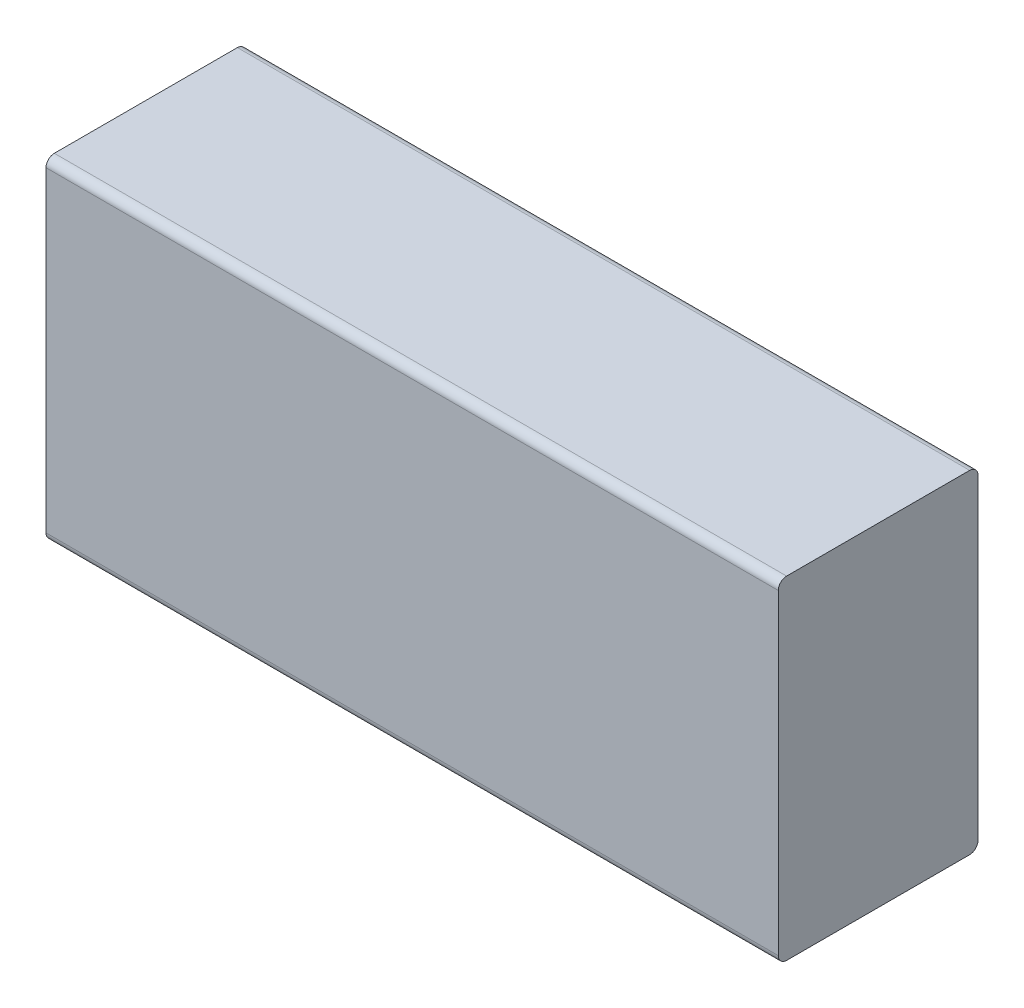
SolidWorks part; units mm, degrees
ref_plane "Front" through (0, 0, 0) normal (0, 0, 1) x (1, 0, 0)
ref_plane "Top" through (0, 0, 0) normal (0, 1, 0) x (1, 0, 0)
ref_plane "Right" through (0, 0, 0) normal (1, 0, 0) x (0, 0, -1)
sketch "Sketch1" plane through (0, 0, 0) normal (0, 0, 1) x (1, 0, 0)
  line L0 (0, 5) -> (-17, 5)
  line L1 (-17, -5) -> (0, -5)
  line L2 (-17, 5) -> (-17, -5)
  arc A2 (0, 5) -> (0, -5) centre (0, 0) cw
  dimension "b" = 10
  dimension "l" = 22
extrude "Extrude1" add sketch "Sketch1" along normal blind 6
sketch "Sketch2" plane through (0, 0, 0) normal (0, 0, 1) x (1, 0, 0)
  line L2 (5, 5) -> (5, -5)
  line L6 (0, 5) -> (-17, 5)
  line L7 (-17, 5) -> (-17, -5)
  line L8 (-17, -5) -> (0, -5)
  line L9 (5, 5) -> (-17, 5)
  line L10 (-17, 5) -> (-17, -5)
  line L11 (-17, -5) -> (5, -5)
  arc A3 (0, -5) -> (0, 5) centre (0, 0) ccw
  arc A4 (0, -5) -> (0, 5) centre (0, 0) ccw construction
  dimension "D1" = 0
extrude "Extrude2" add sketch "Sketch2" along normal blind 6
fillet "Fillet1" radius 0.25 4 edges at (-6, -5, 0) (-6, -5, 6) (-6, 5, 0) (-6, 5, 6)
equation "\"D1@Extrude2\" = \"h@Extrude1\""
